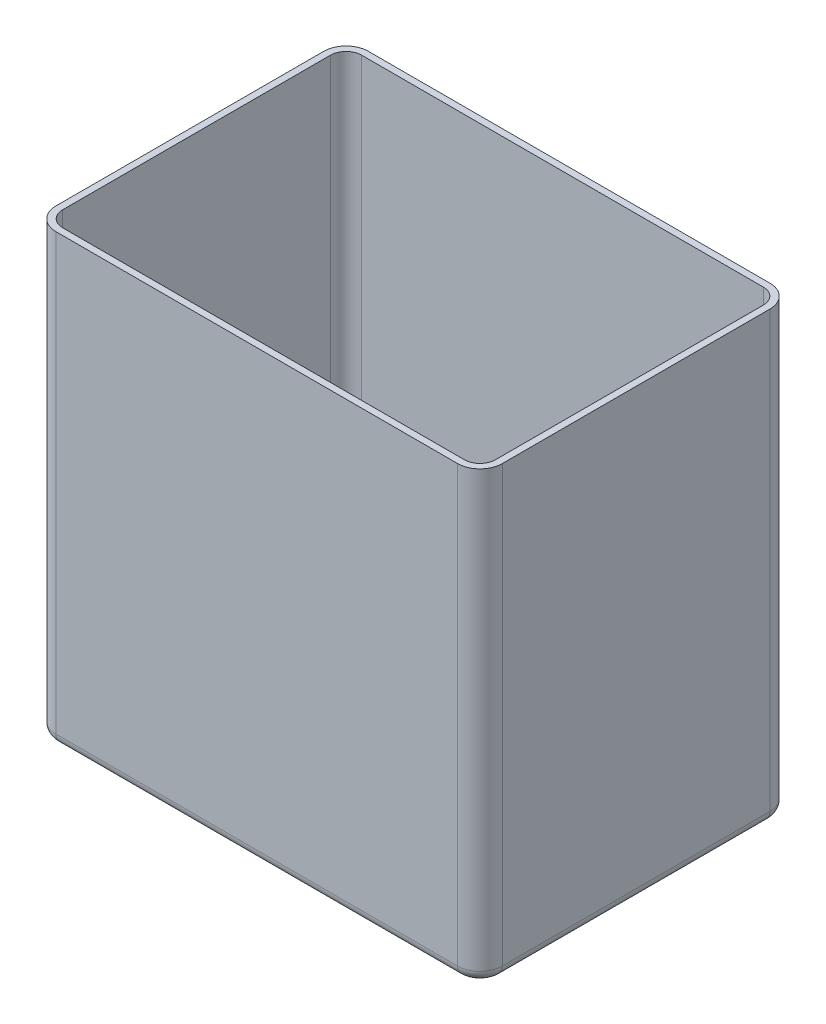
SolidWorks part; units mm, degrees
ref_plane "Alzado" through (0, 0, 0) normal (0, 0, 1) x (1, 0, 0)
ref_plane "Planta" through (0, 0, 0) normal (0, 1, 0) x (1, 0, 0)
ref_plane "Vista lateral" through (0, 0, 0) normal (1, 0, 0) x (0, 0, -1)
sketch "Croquis1" plane through (0, 0, 0) normal (0, 1, 0) x (1, 0, 0)
  line L1 (100, -70) -> (-100, -70)
  line L2 (100, -70) -> (100, 70)
  line L3 (100, 70) -> (-100, 70)
  line L4 (-100, -70) -> (-100, 70)
  line L5 (100, -70) -> (-100, 70) construction
  line L6 (100, 70) -> (-100, -70) construction
  point P0 (0, 0)
  dimension "D1" = 200
  dimension "D2" = 140
extrude "Extruir1" add sketch "Croquis1" against normal blind 200
fillet "Redondeo1" radius 10 4 edges at (-100, -100, 70) (-100, -100, -70) (100, -100, 70) (100, -100, -70)
fillet "Redondeo2" radius 5 8 edges at (97.0711, -200, 67.0711) (100, -200, 0) (97.0711, -200, -67.0711) (0, -200, -70) (-97.0711, -200, -67.0711) (-100, -200, 0) (-97.0711, -200, 67.0711) (0, -200, 70)
shell "Vaciado1" thickness 3
